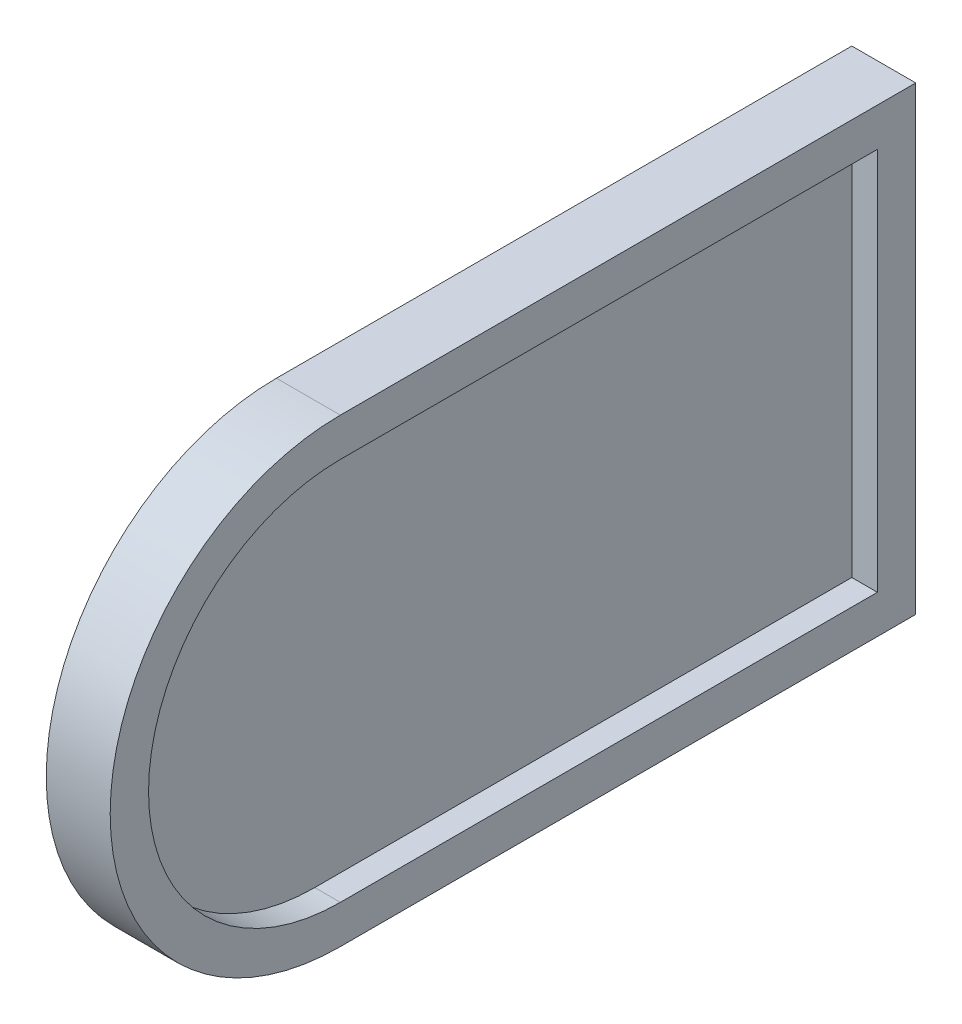
SolidWorks part; units mm, degrees
ref_plane "정면" through (0, 0, 0) normal (0, 0, 1) x (1, 0, 0)
ref_plane "윗면" through (0, 0, 0) normal (0, 1, 0) x (1, 0, 0)
ref_plane "우측면" through (0, 0, 0) normal (1, 0, 0) x (0, 0, -1)
sketch "Sketch1" plane through (0, 0, 0) normal (1, 0, 0) x (0, 0, -1)
  line L0 (0, 18) -> (45, 18)
  line L1 (45, 18) -> (45, -18)
  line L2 (45, -18) -> (0, -18)
  line L3 (0, 15) -> (42, 15) construction
  line L4 (42, 15) -> (42, -15) construction
  line L5 (42, -15) -> (0, -15) construction
  line L6 (0, 18) -> (0, 15) construction
  line L7 (-15, 0) -> (-18, 0) construction
  line L8 (0, -15) -> (0, -18) construction
  line L9 (45, 18) -> (42, 15) construction
  line L10 (45, -18) -> (42, -15) construction
  arc A0 (0, 18) -> (0, -18) centre (0, 0) ccw
  circle A1 centre (0, 0) radius 15 construction
  point P13 (0, 16.5)
  point P14 (-16.5, 0)
  point P15 (0, -16.5)
  point P16 (43.5, 16.5)
  point P17 (43.5, -16.5)
  dimension "D1" = 18
  dimension "D3" = 30
  dimension "D2" = 45
  dimension "D4" = 42
extrude "Boss-Extrude1" add sketch "Sketch1" along normal blind 5
shell "Shell1" thickness 3
